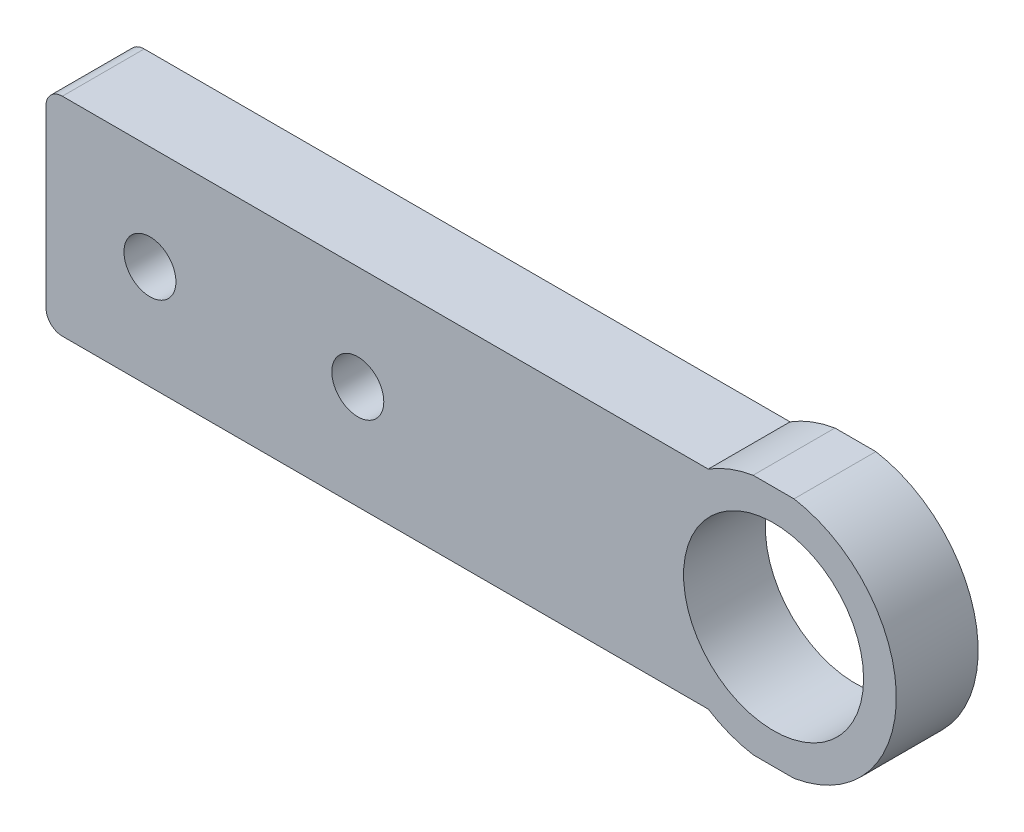
SolidWorks part; units mm, degrees
ref_plane "Front Plane" through (0, 0, 0) normal (0, 0, 1) x (1, 0, 0)
ref_plane "Top Plane" through (0, 0, 0) normal (0, 1, 0) x (1, 0, 0)
ref_plane "Right Plane" through (0, 0, 0) normal (1, 0, 0) x (0, 0, -1)
sketch "Sketch1" plane through (0, 0, 0) normal (0, 0, 1) x (1, 0, 0)
  line L0 (-31.75, 0) -> (-44.45, 0) construction
  line L2 (-44.45, -12.7) -> (-44.45, 12.7)
  line L5 (-44.45, -12.7) -> (44.45, 12.7) construction
  line L6 (-44.45, 12.7) -> (44.45, -12.7) construction
  line L7 (44.45, 12.7) -> (44.45, -12.7) construction
  line L12 (41.95, 14.7902) -> (46.95, 14.7902)
  line L18 (41.95, -14.7902) -> (46.95, -14.7902)
  line L19 (-31.75, 0) -> (-6.35, 0) construction
  line L20 (44.45, -12.7) -> (-44.45, -12.7) construction
  line L21 (44.45, 12.7) -> (-44.45, 12.7) construction
  line L23 (44.45, 14.7902) -> (44.45, -14.7902) construction
  line L25 (36.4681, 12.7) -> (-44.45, 12.7)
  line L26 (36.4681, -12.7) -> (-44.45, -12.7)
  circle A0 centre (-31.75, 0) radius 3.175
  circle A6 centre (44.45, 0) radius 11
  circle A12 centre (-6.35, 0) radius 3.175
  circle A13 centre (44.45, 0) radius 15 construction
  arc A15 (46.95, -14.7902) -> (46.95, 14.7902) centre (44.45, 0) ccw
  arc A16 (41.95, 14.7902) -> (36.4681, 12.7) centre (44.45, 0) ccw
  arc A17 (41.95, -14.7902) -> (36.4681, -12.7) centre (44.45, 0) cw
  point P0 (0, 0)
  dimension "D4" = 6.35
  dimension "D8" = 22
  dimension "D5" = 4
  dimension "D6" = 5
  dimension "D2" = 50.8
  dimension "D3" = 12.7
  dimension "D12" = 25.4
  dimension "D13" = 25.4
extrude "Boss-Extrude1" add sketch "Sketch1" along normal blind 10
fillet "Fillet3" radius 2 2 edges at (-44.45, -12.7, 5) (-44.45, 12.7, 5)
